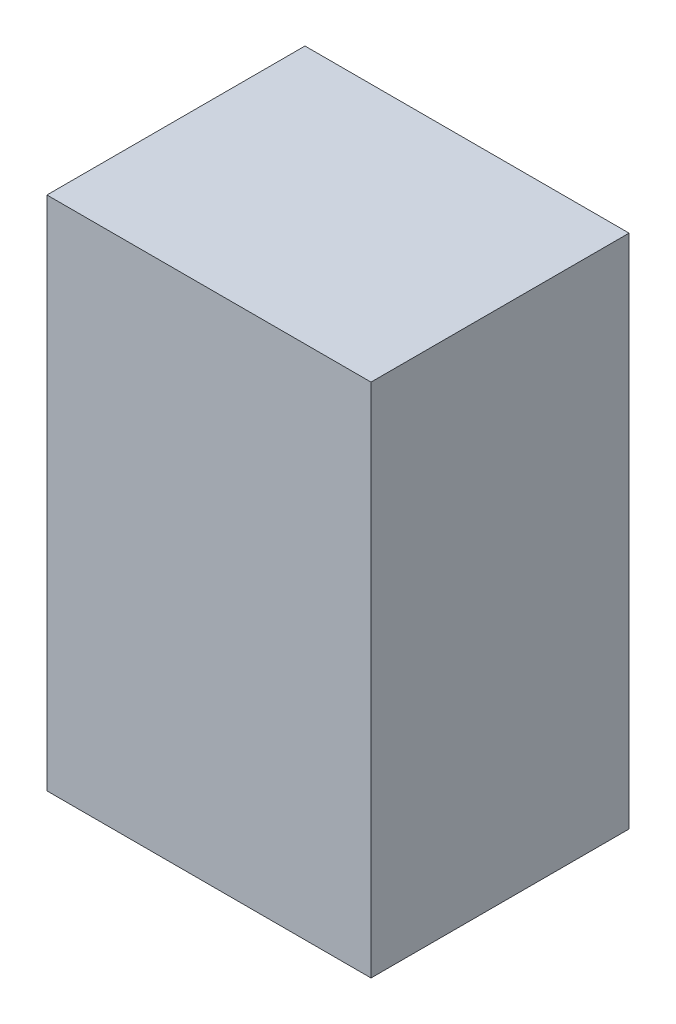
SolidWorks part; units mm, degrees
ref_plane "前视基准面" through (0, 0, 0) normal (0, 0, 1) x (1, 0, 0)
ref_plane "上视基准面" through (0, 0, 0) normal (0, 1, 0) x (1, 0, 0)
ref_plane "右视基准面" through (0, 0, 0) normal (1, 0, 0) x (0, 0, -1)
sketch "草图3" plane through (0, 0, 0) normal (0, 1, 0) x (1, 0, 0)
  line L1 (-55.2788, 15.9897) -> (7.5212, 15.9897)
  line L2 (-55.2788, 15.9897) -> (-55.2788, -34.0103)
  line L3 (-55.2788, -34.0103) -> (7.5212, -34.0103)
  line L4 (7.5212, 15.9897) -> (7.5212, -34.0103)
extrude "凸台-拉伸1" add sketch "草图3" along normal blind 100
